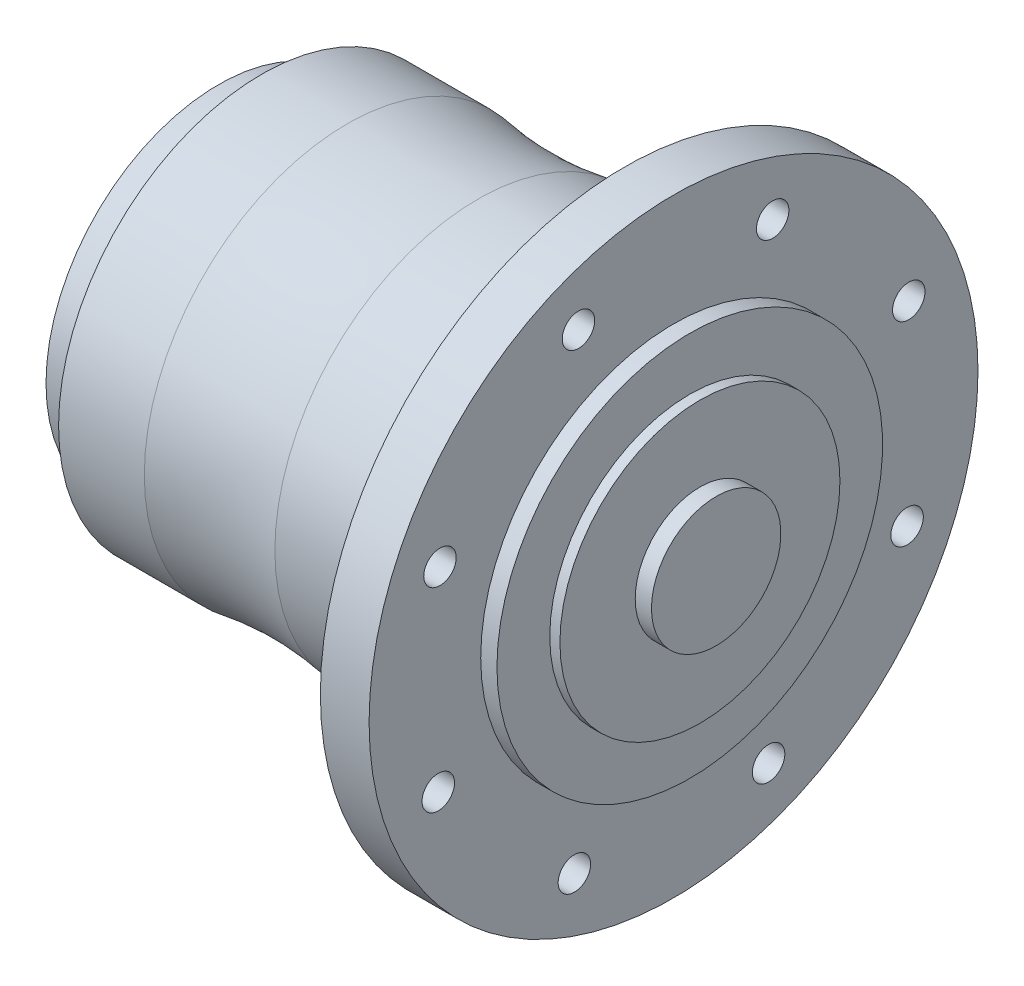
SolidWorks part; units mm, degrees
ref_plane "Ön Düzlem" through (0, 0, 0) normal (0, 0, 1) x (1, 0, 0)
ref_plane "Üst Düzlem" through (0, 0, 0) normal (0, 1, 0) x (1, 0, 0)
ref_plane "Sağ Düzlem" through (0, 0, 0) normal (1, 0, 0) x (0, 0, -1)
sketch "Çizim1" plane through (0, 0, 0) normal (0, 0, 1) x (1, 0, 0)
  line L0 (0, 0) -> (0, 40)
  line L1 (0, 40) -> (8, 40)
  line L2 (8, 40) -> (8, 55)
  line L3 (8, 55) -> (15.3342, 55)
  line L4 (15.3342, 55) -> (15.3342, 85)
  line L5 (15.3342, 85) -> (36.525, 85)
  line L6 (36.525, 85) -> (36.525, 100)
  line L7 (36.525, 100) -> (78.7526, 100)
  line L8 (143.0833, 100) -> (215.5, 100)
  line L9 (215.5, 100) -> (215.5, 150)
  line L10 (215.5, 150) -> (239.5, 150)
  line L11 (239.5, 150) -> (239.5, 95)
  line L12 (239.5, 95) -> (247.5, 95)
  line L13 (247.5, 95) -> (247.5, 68.9847)
  line L14 (247.5, 68.9847) -> (252.5, 68.9847)
  line L15 (252.5, 68.9847) -> (252.5, 31.8698)
  line L16 (252.5, 31.8698) -> (260.5, 31.8698)
  line L17 (260.5, 31.8698) -> (260.5, 0)
  line L18 (0, 0) -> (260.5, 0) construction
  line L19 (0, 0) -> (260.5, 0)
  arc A0 (78.7526, 100) -> (143.0833, 100) centre (110.9179, 296.2423) ccw
  dimension "D1" = 252.5
  dimension "D2" = 8
  dimension "D3" = 5
  dimension "D4" = 8
  dimension "D5" = 95
  dimension "D6" = 24
  dimension "D7" = 55
  dimension "D8" = 150
  dimension "D9" = 100
  dimension "D11" = 15
revolve "Döndür1" add sketch "Çizim1" angle 360 about L18
sketch "Çizim2" plane through (215.5, 0, 0) normal (-1, 0, 0) x (0, 0, 1)
  line L0 (0, 0) -> (0, 151.96)
  line L1 (0, 0) -> (58.1339, 143.8865)
  circle A0 centre (0, 0) radius 125
  circle A1 centre (46.8258, 115.898) radius 8
  dimension "D1" = 250
  dimension "D3" = 16
  dimension "D2" = 22
extrude "Kes-Ekstrüzyon1" cut sketch "Çizim2" against normal up to next contours L1 A1 A0 | A0 A1 L1 | L1 A1 A0 | A0 A1 L1
pattern_circular "Dairesel Çoğaltma1" count 8 over 360 about axis through (0, 0, 0) along (1, 0, 0) of "Kes-Ekstrüzyon1"
